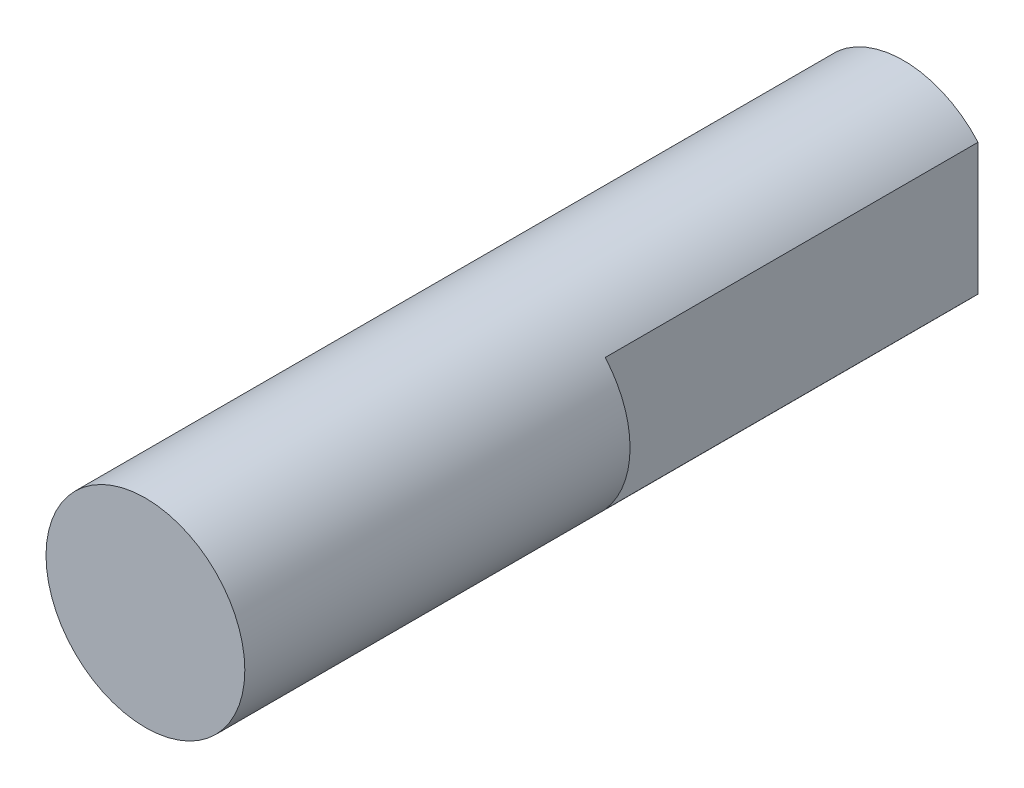
SolidWorks part; units mm, degrees
material "201 강화 스테인리스 강 (SS)"
ref_plane "정면" through (0, 0, 0) normal (0, 0, 1) x (1, 0, 0)
ref_plane "윗면" through (0, 0, 0) normal (0, 1, 0) x (1, 0, 0)
ref_plane "우측면" through (0, 0, 0) normal (1, 0, 0) x (0, 0, -1)
sketch "스케치1" plane through (0, 0, 0) normal (0, 0, 1) x (1, 0, 0)
  circle A0 centre (0, 0) radius 4
  dimension "D1" = 8
extrude "보스-돌출1" add sketch "스케치1" along normal blind 10 and the other way blind 20.5
sketch "스케치3" plane through (0, 0, -20.5) normal (0, 0, -1) x (-1, 0, 0)
  line L0 (-3, 2.6458) -> (-3, -2.6458)
  line L1 (4, 0) -> (4, 8.1981) construction
  circle A0 centre (0, 0) radius 4 construction
  arc A1 (-3, 2.6458) -> (-3, -2.6458) centre (0, 0) ccw
  circle M3 centre (0, 0) radius 4
  dimension "D1" = 4
  dimension "D2" = 7
extrude "컷-돌출1" cut sketch "스케치3" against normal blind 15 contours L0 M3
